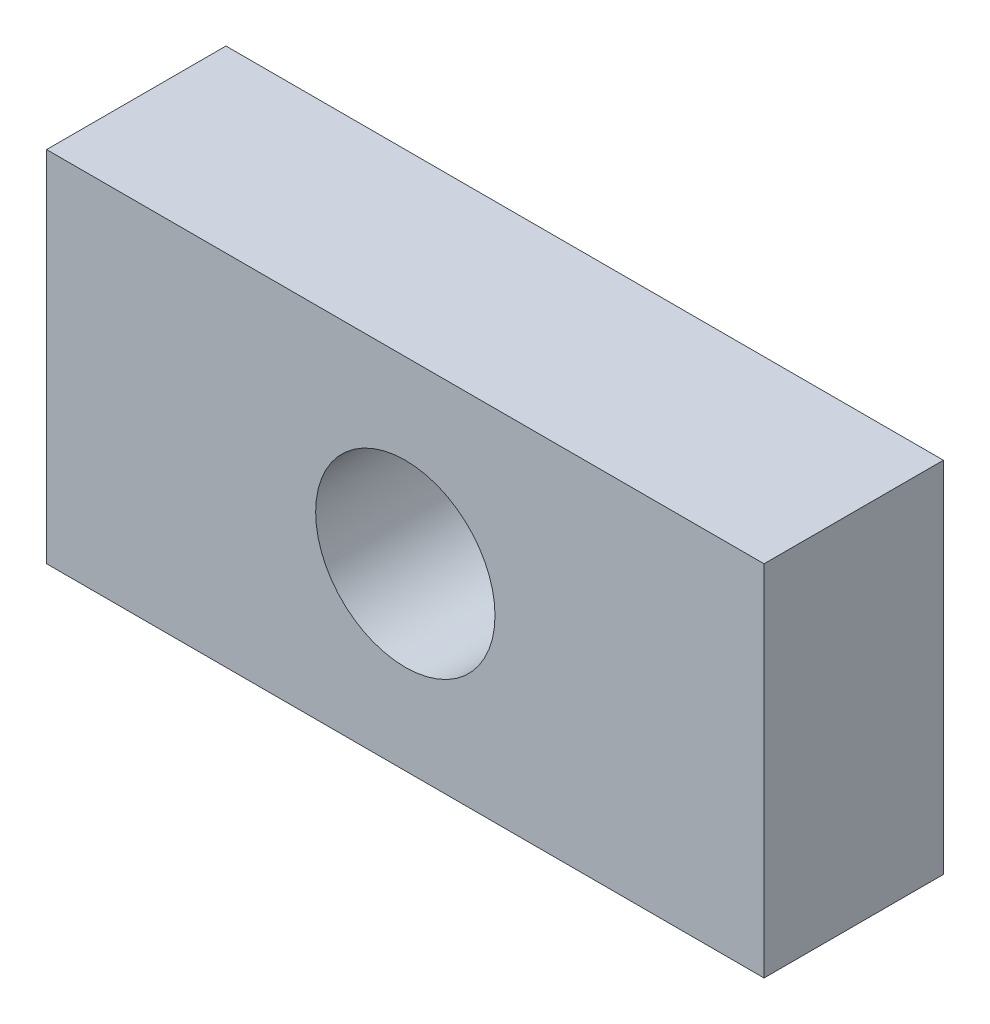
SolidWorks part; units mm, degrees
material "1060 Alloy"
ref_plane "Front Plane" through (0, 0, 0) normal (0, 0, 1) x (1, 0, 0)
ref_plane "Top Plane" through (0, 0, 0) normal (0, 1, 0) x (1, 0, 0)
ref_plane "Right Plane" through (0, 0, 0) normal (1, 0, 0) x (0, 0, -1)
sketch "Sketch1" plane through (0, 0, 0) normal (0, 0, 1) x (1, 0, 0)
  line L1 (0, 0) -> (40, 0)
  line L2 (0, 0) -> (0, 20)
  line L3 (0, 20) -> (40, 20)
  line L4 (40, 0) -> (40, 20)
  dimension "D1" = 40
  dimension "D2" = 20
extrude "Boss-Extrude1" add sketch "Sketch1" along normal blind 10
sketch "Sketch2" plane through (0, 0, 10) normal (0, 0, 1) x (1, 0, 0)
  line L0 (0, 20) -> (0, 0) construction
  line L1 (0, 20) -> (0, 0) construction
  line L2 (40, 20) -> (0, 20) construction
  line L3 (40, 20) -> (0, 20) construction
  circle A0 centre (20, 10) radius 5
  point P2 (0, 0)
  point P6 (0, 10)
  point P7 (20, 20)
  dimension "Bore" = 10
extrude "Cut-Extrude1" cut sketch "Sketch2" against normal through all
equation "\"block_len\"= 40"
equation "\"D1@Sketch1\"=\"block_len\""
